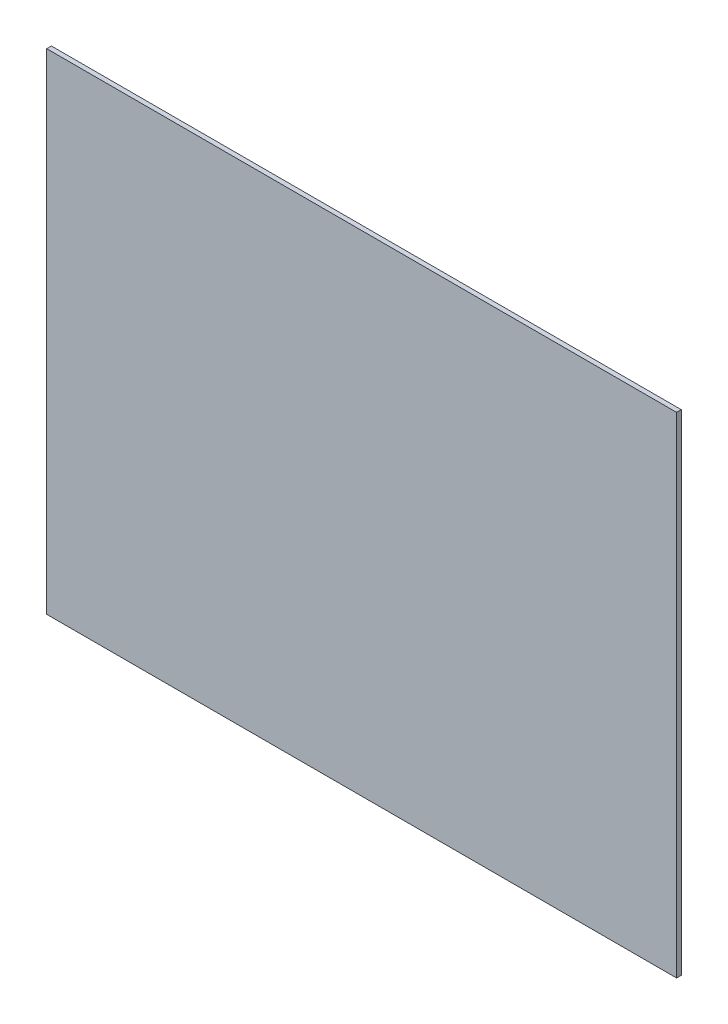
SolidWorks part; units mm, degrees
ref_plane "Спереди" through (0, 0, 0) normal (0, 0, 1) x (1, 0, 0)
ref_plane "Сверху" through (0, 0, 0) normal (0, 1, 0) x (1, 0, 0)
ref_plane "Справа" through (0, 0, 0) normal (1, 0, 0) x (0, 0, -1)
sketch "Эскиз1" plane through (0, 0, 0) normal (0, 0, 1) x (1, 0, 0)
  line L1 (-270, -210) -> (270, -210)
  line L2 (-270, -210) -> (-270, 210)
  line L3 (-270, 210) -> (270, 210)
  line L4 (270, -210) -> (270, 210)
  line L5 (-270, -210) -> (270, 210) construction
  line L6 (-270, 210) -> (270, -210) construction
  point P0 (0, 0)
  dimension "D1" = 540
  dimension "D2" = 420
extrude "Бобышка-Вытянуть1" add sketch "Эскиз1" along normal blind 4
